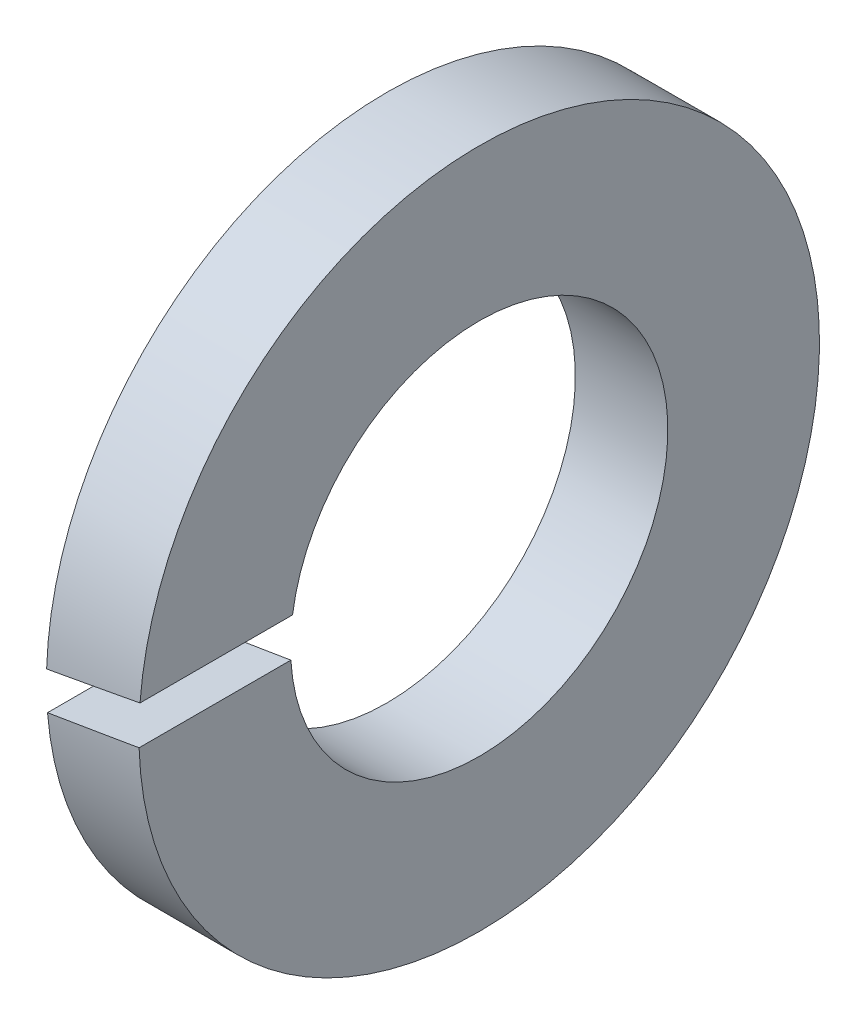
SolidWorks part; units mm, degrees
ref_plane "Front" through (0, 0, 0) normal (0, 0, 1) x (1, 0, 0)
ref_plane "Top" through (0, 0, 0) normal (0, 1, 0) x (1, 0, 0)
ref_plane "Right" through (0, 0, 0) normal (1, 0, 0) x (0, 0, -1)
sketch "Sketch1" plane through (0, 0, 0) normal (0, 0, 1) x (1, 0, 0)
  line L0 (-1.25, 5.1) -> (1.25, 5.1)
  line L1 (1.25, 5.1) -> (1.25, 9.2)
  line L2 (1.25, 9.2) -> (-1.25, 9.2)
  line L3 (-1.25, 9.2) -> (-1.25, 5.1)
  line L4 (1.25, 0) -> (-1.25, 0) construction
  line L5 (0, 0) -> (0, 3.8863) construction
  dimension "D1" = 10.2
  dimension "D2" = 18.4
  dimension "D3" = 2.5
revolve "Revolve1" add sketch "Sketch1" angle 360 about L4
sketch "Sketch2" plane through (0, 0, 0) normal (0, 0, 1) x (1, 0, 0)
  line L0 (-1.4271, 0.2662) -> (-1.25, -0.7383)
  line L1 (-1.25, -0.7383) -> (1.4271, -0.2662)
  line L2 (1.4271, -0.2662) -> (1.25, 0.7383)
  line L3 (1.25, 0.7383) -> (-1.4271, 0.2662)
  line L4 (0, 0) -> (4.1653, 0) construction
  line L5 (1.3386, 0.236) -> (-1.3386, -0.236) construction
  line L6 (-1.25, 9.2) -> (-1.25, -9.2) construction
  line L7 (1.25, -9.2) -> (1.25, 9.2) construction
  dimension "D1" = 10
  dimension "D2" = 1.02
extrude "Cut-Extrude1" cut sketch "Sketch2" along normal blind 18.4
